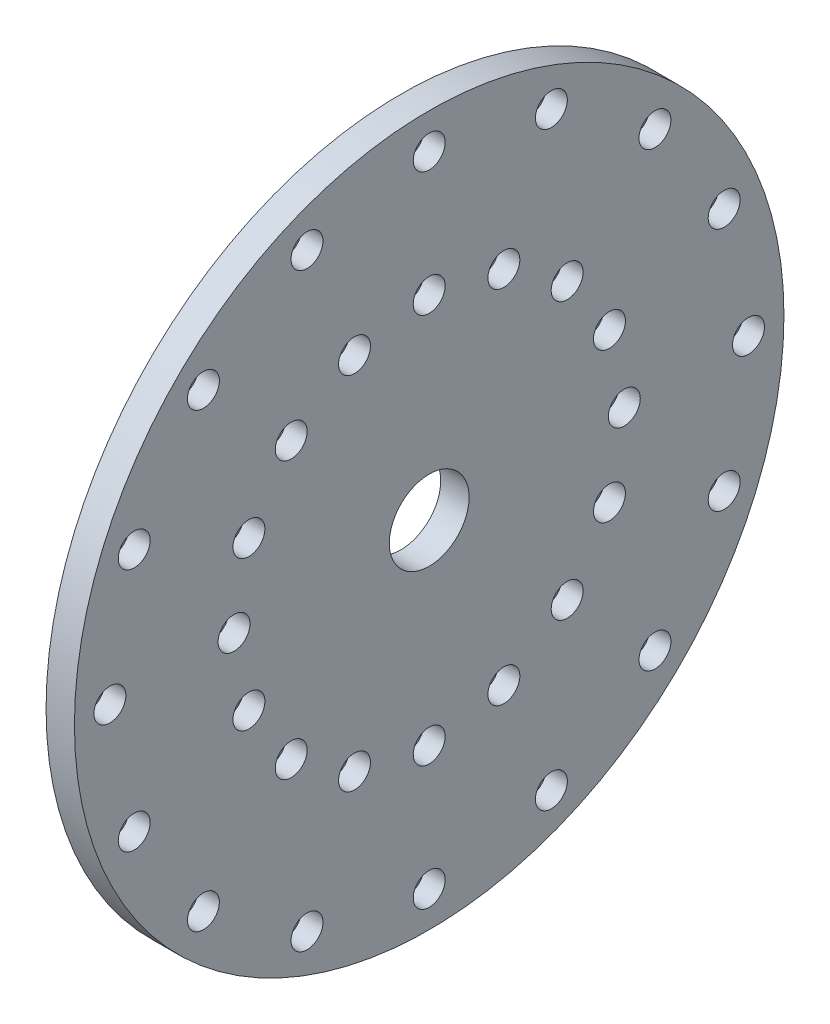
SolidWorks part; units mm, degrees
material "ASTM A36 Steel"
ref_plane "Front Plane" through (0, 0, 0) normal (0, 0, 1) x (1, 0, 0)
ref_plane "Top Plane" through (0, 0, 0) normal (0, 1, 0) x (1, 0, 0)
ref_plane "Right Plane" through (0, 0, 0) normal (1, 0, 0) x (0, 0, -1)
sketch "Sketch1" plane through (0, 0, 0) normal (1, 0, 0) x (0, 0, -1)
  circle A0 centre (0, 0) radius 200
  dimension "D1" = 400
extrude "Boss-Extrude1" add sketch "Sketch1" along normal blind 16
sketch "Sketch2" plane through (16, 0, 0) normal (1, 0, 0) x (0, 0, -1)
  circle A0 centre (0, 0) radius 22.5
  dimension "D1" = 45
extrude "Cut-Extrude1" cut sketch "Sketch2" against normal through all both and the other way through all
sketch "Sketch3" plane through (16, 0, 0) normal (1, 0, 0) x (0, 0, -1)
  circle A1 centre (110, 0) radius 6
  dimension "D2" = 12
extrude "Cut-Extrude2" cut sketch "Sketch3" against normal through all both and the other way through all
pattern_circular "CirPattern1" count 16 over 360 about axis through (0, 0, 0) along (1, 0, 0) of "Cut-Extrude2"
sketch "Sketch4" plane through (16, 0, 0) normal (1, 0, 0) x (0, 0, -1)
  circle A1 centre (180, 0) radius 6
  dimension "D1" = 12
extrude "Cut-Extrude3" cut sketch "Sketch4" against normal through all both and the other way through all
pattern_circular "CirPattern2" count 16 over 360 about axis through (0, 0, 0) along (1, 0, 0) of "Cut-Extrude3"
sketch "Sketch5" plane through (16, 0, 0) normal (1, 0, 0) x (0, 0, -1)
  circle A0 centre (166.2983, 68.883) radius 9
  dimension "D1" = 18
extrude "Cut-Extrude4" cut sketch "Sketch5" against normal blind 12
pattern_circular "CirPattern3" count 16 over 360 about axis through (0, 0, 0) along (1, 0, 0) of "Cut-Extrude4"
sketch "Sketch6" plane through (16, 0, 0) normal (1, 0, 0) x (0, 0, -1)
  circle A0 centre (101.6267, 42.0952) radius 9
  dimension "D1" = 18
extrude "Cut-Extrude5" cut sketch "Sketch6" against normal blind 12
pattern_circular "CirPattern4" count 16 over 360 about axis through (0, 0, 0) along (1, 0, 0) of "Cut-Extrude5"
